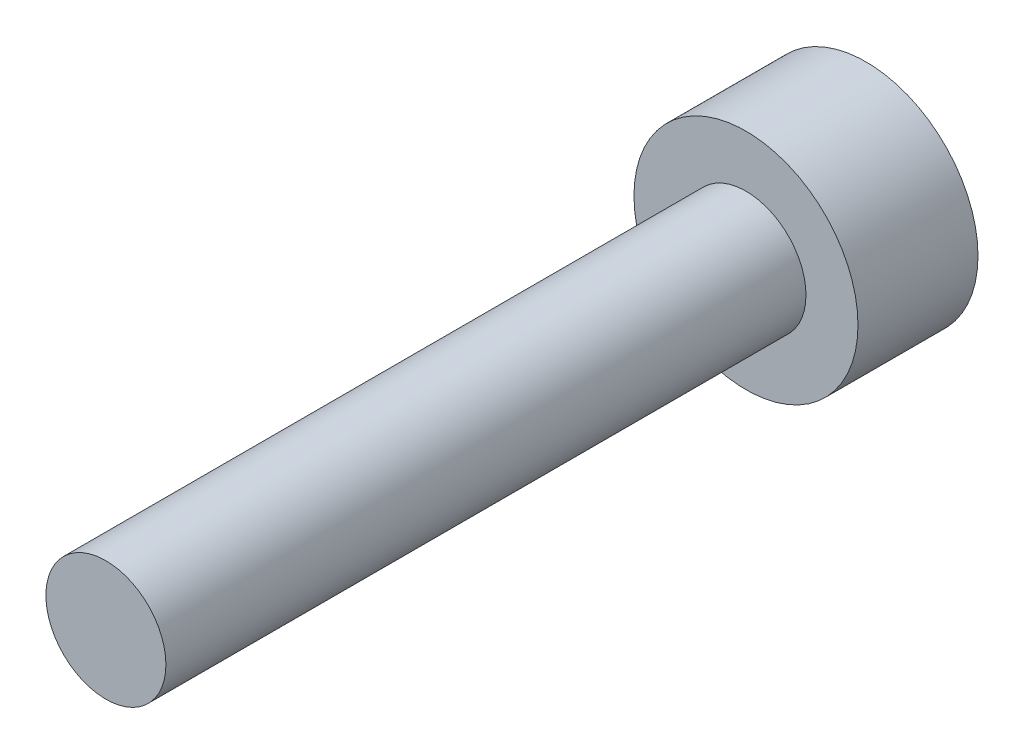
SolidWorks part; units mm, degrees
ref_plane "Front Plane" through (0, 0, 0) normal (0, 0, 1) x (1, 0, 0)
ref_plane "Top Plane" through (0, 0, 0) normal (0, 1, 0) x (1, 0, 0)
ref_plane "Right Plane" through (0, 0, 0) normal (1, 0, 0) x (0, 0, -1)
sketch "Sketch1" plane through (0, 0, 0) normal (0, 0, 1) x (1, 0, 0)
  circle A0 centre (0, 0) radius 2.8
extrude "Head" add sketch "Sketch1" along normal blind 3 from offset 3
sketch "Sketch2" plane through (0, 0, 0) normal (0, 0, 1) x (1, 0, 0)
  circle A0 centre (0, 0) radius 1.5
extrude "Shank" add sketch "Sketch2" along normal blind 16
sketch "Sketch3" plane through (0, 0, 0) normal (0, 0, 1) x (1, 0, 0)
  line L0 (1.25, 0.7217) -> (0, 1.4434)
  line L1 (0, 1.4434) -> (-1.25, 0.7217)
  line L2 (-1.25, 0.7217) -> (-1.25, -0.7217)
  line L3 (-1.25, -0.7217) -> (0, -1.4434)
  line L4 (0, -1.4434) -> (1.25, -0.7217)
  line L5 (1.25, -0.7217) -> (1.25, 0.7217)
extrude "Hex socket" cut sketch "Sketch3" along normal blind 1.8 from offset 3.2
